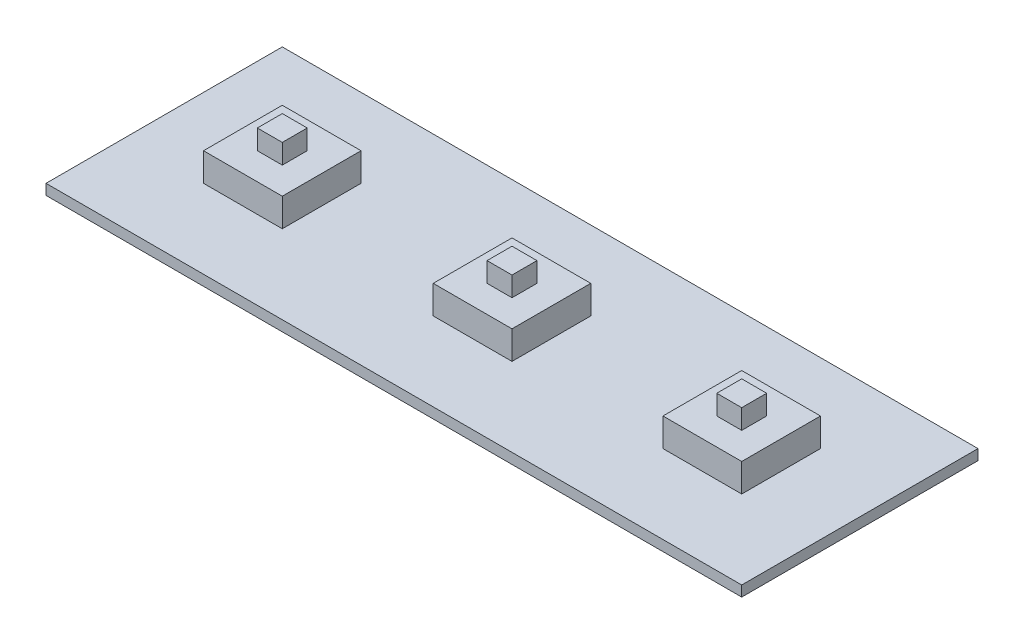
SolidWorks part; units mm, degrees
ref_plane "Front Plane" through (0, 0, 0) normal (0, 0, 1) x (1, 0, 0)
ref_plane "Top Plane" through (0, 0, 0) normal (0, 1, 0) x (1, 0, 0)
ref_plane "Right Plane" through (0, 0, 0) normal (1, 0, 0) x (0, 0, -1)
sketch "Sketch1" plane through (0, 0, 0) normal (0, 1, 0) x (1, 0, 0)
  line L1 (0, 0) -> (12, 0)
  line L2 (0, 0) -> (0, 12)
  line L3 (0, 12) -> (12, 12)
  line L4 (12, 0) -> (12, 12)
  dimension "D1" = 12
  dimension "D2" = 12
extrude "Boss-Extrude1" add sketch "Sketch1" along normal blind 4.3
sketch "Sketch2" plane through (0, 4.3, 0) normal (0, 1, 0) x (1, 0, 0)
  line L1 (4.1, 7.9) -> (7.9, 7.9)
  line L2 (4.1, 7.9) -> (4.1, 4.1)
  line L3 (4.1, 4.1) -> (7.9, 4.1)
  line L4 (7.9, 7.9) -> (7.9, 4.1)
  line L5 (0, 12) -> (0, 0) construction
  line L6 (12, 12) -> (0, 12) construction
  circle A0 centre (6, 6) radius 2.687
  point P6 (0, 0)
  point P7 (0, 0)
  dimension "D1" = 3.8
  dimension "D2" = 3.8
  dimension "D3" = 6
  dimension "D4" = 6
extrude "Boss-Extrude2" add sketch "Sketch2" along normal blind 3 contours L4 L1 L2 L3
sketch "Sketch3" plane through (0, 0, 0) normal (0, -1, 0) x (1, 0, 0)
  line L0 (0, -12) -> (0, 0) construction
  line L1 (-12, 12) -> (94, 12)
  line L2 (-12, 12) -> (-12, -24)
  line L3 (-12, -24) -> (94, -24)
  line L4 (94, 12) -> (94, -24)
  line L5 (0, 0) -> (12, 0) construction
  line L6 (12, -12) -> (0, -12) construction
  dimension "D1" = 12
  dimension "D2" = 12
  dimension "D3" = 12
  dimension "D4" = 106
extrude "Boss-Extrude3" add sketch "Sketch3" along normal blind 1.6
sketch "Sketch4" plane through (0, 0, 0) normal (0, 1, 0) x (1, 0, 0)
  line L1 (35, 12) -> (47, 12)
  line L2 (35, 12) -> (35, 0)
  line L3 (35, 0) -> (47, 0)
  line L4 (47, 12) -> (47, 0)
  line L5 (0, 12) -> (0, 0) construction
  line L6 (12, 12) -> (0, 12) construction
  line L7 (70, 12) -> (82, 12)
  line L8 (70, 12) -> (70, 0)
  line L9 (70, 0) -> (82, 0)
  line L10 (82, 12) -> (82, 0)
  line L11 (12, 12) -> (0, 12) construction
  line L12 (94, 24) -> (94, -12) construction
  dimension "D1" = 35
  dimension "D2" = 35
  dimension "D3" = 12
  dimension "D4" = 12
  dimension "D5" = 12
  dimension "D6" = 12
  dimension "D7" = 0
  dimension "D8" = 0
extrude "Boss-Extrude4" add sketch "Sketch4" along normal blind 4.3
sketch "Sketch5" plane through (0, 4.3, 0) normal (0, 1, 0) x (1, 0, 0)
  line L1 (39.1, 7.9) -> (42.9, 7.9)
  line L2 (39.1, 7.9) -> (39.1, 4.1)
  line L3 (39.1, 4.1) -> (42.9, 4.1)
  line L4 (42.9, 7.9) -> (42.9, 4.1)
  line L5 (74.1, 7.9) -> (77.9, 7.9)
  line L6 (74.1, 7.9) -> (74.1, 4.1)
  line L7 (74.1, 4.1) -> (77.9, 4.1)
  line L8 (77.9, 7.9) -> (77.9, 4.1)
  line L9 (35, 12) -> (35, 0) construction
  line L10 (47, 12) -> (35, 12) construction
  line L11 (82, 12) -> (70, 12) construction
  line L12 (70, 12) -> (70, 0) construction
  dimension "D1" = 3.8
  dimension "D2" = 4.1
  dimension "D3" = 4.1
  dimension "D4" = 3.8
  dimension "D5" = 3.8
  dimension "D6" = 4.1
  dimension "D7" = 4.1
extrude "Boss-Extrude5" add sketch "Sketch5" along normal blind 3 contours L2 L1 L4 L3 | L6 L5 L8 L7
